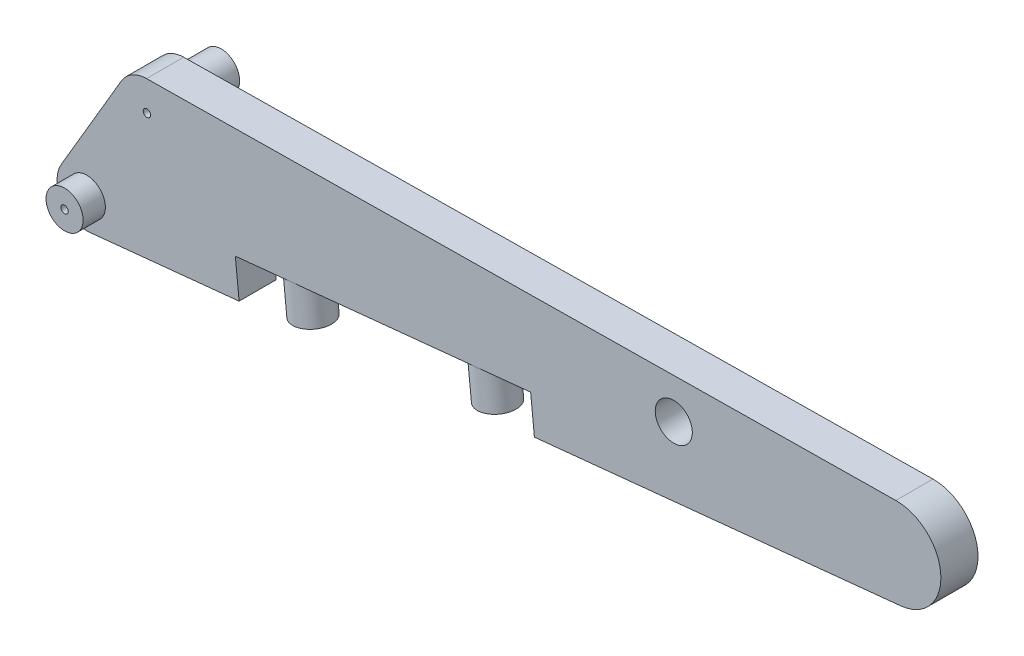
SolidWorks part; units mm, degrees
material "ABS"
ref_plane "Front Plane" through (0, 0, 0) normal (0, 0, 1) x (1, 0, 0)
ref_plane "Top Plane" through (0, 0, 0) normal (0, 1, 0) x (1, 0, 0)
ref_plane "Right Plane" through (0, 0, 0) normal (1, 0, 0) x (0, 0, -1)
sketch "Sketch2" plane through (0, 0, 0) normal (0, 0, 1) x (1, 0, 0)
  line L0 (-8.1022, -13.7969) -> (0, 0)
  line L1 (0, 0) -> (101, -0.7468)
  dimension "D1" = 101
  dimension "D2" = 16
  dimension "D3" = 120
sketch "Sketch3" plane through (0, 0, 0) normal (0, 0, 1) x (1, 0, 0)
  line L0 (-11.5515, -11.7713) -> (-3.4492, 2.0256)
  line L1 (-0.0496, 3.9997) -> (100.9255, 5.2527)
  line L2 (101.604, -6.7163) -> (-7.6995, -17.7766)
  circle A0 centre (-8.1022, -13.7969) radius 2.5
  arc A1 (-11.5515, -11.7713) -> (-7.6995, -17.7766) centre (-8.1022, -13.7969) ccw
  circle A2 centre (0, 0) radius 2.5
  arc A3 (-0.0496, 3.9997) -> (-3.4492, 2.0256) centre (0, 0) ccw
  arc A4 (101.604, -6.7163) -> (100.9255, 5.2527) centre (101, -0.7468) ccw
  dimension "D1" = 5
  dimension "D2" = 8
  dimension "D3" = 5
  dimension "D4" = 8
  dimension "D5" = 12
extrude "Boss-Extrude1" add sketch "Sketch3" along normal blind 5
sketch "Sketch4" plane through (0, 0, 5) normal (0, 0, 1) x (1, 0, 0)
  circle A0 centre (0, 0) radius 2.5
  circle A1 centre (0, 0) radius 0.5
  dimension "D1" = 1
  dimension "D2" = 5
extrude "Boss-Extrude2" add sketch "Sketch4" against normal blind 10
sketch "Sketch5" plane through (0, 0, 0) normal (0, 0, -1) x (-1, 0, 0)
  circle A0 centre (8.1022, -13.7969) radius 2.5
  circle A1 centre (8.1022, -13.7969) radius 0.5
  dimension "D1" = 1
  dimension "D2" = 5
extrude "Boss-Extrude3" add sketch "Sketch5" against normal blind 8
sketch "Sketch6" plane through (0, 0, 0) normal (0, 0, -1) x (-1, 0, 0)
  line L0 (0, 0) -> (-101, -0.7468) construction
  circle A1 centre (-71, -0.525) radius 2.5
  dimension "D1" = 5
  dimension "D2" = 30
extrude "Cut-Extrude1" cut sketch "Sketch6" against normal blind 5
sketch "Sketch7" plane through (0, 0, 0) normal (0, 0, -1) x (-1, 0, 0)
  line L0 (-52.2175, -11.7136) -> (-12.4208, -15.7406)
  line L1 (-52.2175, -11.7136) -> (-51.7116, -6.7136)
  line L2 (-12.4208, -15.7406) -> (-11.9148, -10.7406)
  line L3 (-51.7116, -6.7136) -> (-11.9148, -10.7406)
  line L4 (7.6995, -17.7766) -> (-101.604, -6.7163) construction
  dimension "D1" = 50
  dimension "D2" = 5
  dimension "D3" = 40
extrude "Cut-Extrude2" cut sketch "Sketch7" against normal blind 5
sketch "Sketch8" plane through (1.1966, -11.8252, 0) normal (0.1007, -0.9949, 0) x (0.9949, 0.1007, 0)
  line L0 (10.773, 0) -> (50.773, 0) construction
  line L1 (50.773, 5) -> (50.773, 0) construction
  line L2 (10.773, 5) -> (10.773, 0) construction
  circle A0 centre (18.273, 2.5) radius 2.5
  circle A1 centre (18.273, 2.5) radius 0.5
  circle A2 centre (43.273, 2.5) radius 0.5
  circle A3 centre (43.273, 2.5) radius 2.5
  dimension "D1" = 5
  dimension "D2" = 1
  dimension "D6" = 1
  dimension "D7" = 5
  dimension "D3" = 2.5
  dimension "D4" = 7.5
  dimension "D5" = 2.5
  dimension "D8" = 7.5
extrude "Boss-Extrude4" add sketch "Sketch8" along normal blind 5
